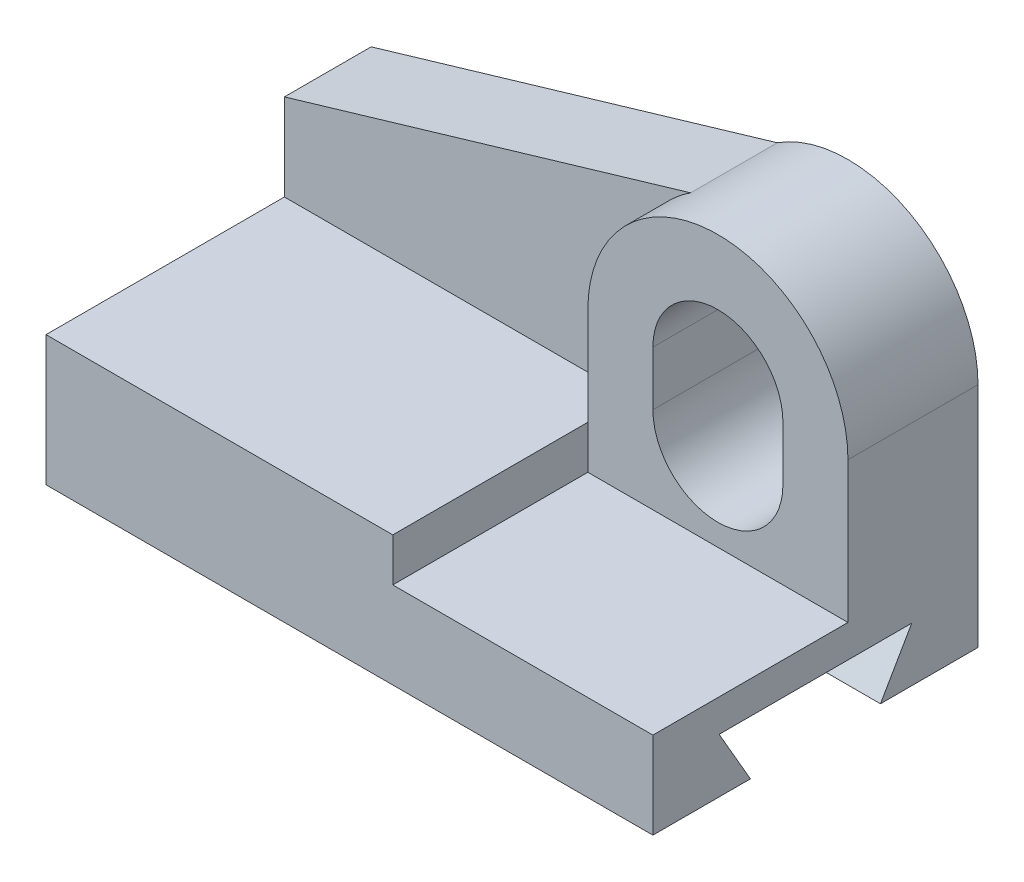
SolidWorks part; units mm, degrees
ref_plane "前视基准面" through (0, 0, 0) normal (0, 0, 1) x (1, 0, 0)
ref_plane "上视基准面" through (0, 0, 0) normal (0, 1, 0) x (1, 0, 0)
ref_plane "右视基准面" through (0, 0, 0) normal (1, 0, 0) x (0, 0, -1)
other "Configuration Table"
sketch "草图2" plane through (0, 0, 0) normal (0, 1, 0) x (1, 0, 0)
  line L1 (0, 0) -> (56, 0)
  line L2 (0, 0) -> (0, -30)
  line L3 (0, -30) -> (56, -30)
  line L4 (56, 0) -> (56, -30)
  dimension "D1" = 56
  dimension "D2" = 30
extrude "凸台-拉伸2" add sketch "草图2" along normal blind 12
sketch "草图4" plane through (0, 0, 0) normal (-1, 0, 0) x (0, 0, 1)
  line L0 (9, 0) -> (21, 0)
  line L1 (0, 0) -> (30, 0) construction
  line L2 (21, 0) -> (23.8868, 5)
  line L3 (23.8868, 5) -> (6.1132, 5)
  line L4 (6.1132, 5) -> (9, 0)
  point P5 (15, 0)
  dimension "D1" = 15
  dimension "D2" = 12
  dimension "D3" = 60
  dimension "D4" = 5
  dimension "D5" = 60
extrude "切除-拉伸1" cut sketch "草图4" against normal through all
sketch "草图6" plane through (0, 12, 0) normal (0, 1, 0) x (1, 0, 0)
  line L0 (0, 0) -> (0, -8)
  line L1 (0, 0) -> (0, -30) construction
  line L2 (0, -8) -> (56, -8)
  line L3 (56, -30) -> (56, 0) construction
  line L4 (56, -8) -> (56, 0)
  line L5 (56, 0) -> (0, 0) construction
  line L6 (56, 0) -> (0, 0)
  line L7 (56, 0) -> (32, 0)
  line L8 (32, 0) -> (32, -30)
  line L9 (0, -30) -> (56, -30) construction
  line L10 (32, -30) -> (56, -30)
  line L11 (56, -30) -> (56, 0)
extrude "切除-拉伸2" cut sketch "草图6" against normal blind 4 contours L7 L8 L10 L11
sketch "草图8" plane through (0, 12, 0) normal (0, 1, 0) x (1, 0, 0)
  line L0 (0, 0) -> (0, -8)
  line L1 (0, 0) -> (0, -30) construction
extrude "拉伸-薄壁1" add sketch "草图8" along normal blind 8 thin thin type one direction reverse wall 10
sketch "草图9" plane through (0, 8, 0) normal (0, 1, 0) x (1, 0, 0)
  line L0 (32, 0) -> (32, -12)
  line L1 (32, 0) -> (32, -30) construction
  line L2 (32, -12) -> (56, -12)
  line L3 (56, -30) -> (56, 0) construction
  line L4 (56, -12) -> (56, 0)
  line L5 (56, 0) -> (32, 0)
extrude "凸台-拉伸3" add sketch "草图9" along normal blind 13
sketch "草图10" plane through (0, 0, 12) normal (0, 0, 1) x (1, 0, 0)
  line L0 (32, 21) -> (56, 21) construction
  circle A0 centre (44, 21) radius 12
extrude "凸台-拉伸4" add sketch "草图10" against normal up to vertex (12 mm away) up to point (32, 21, 0)
sketch "草图13" plane through (0, 0, 0) normal (0, 0, -1) x (-1, 0, 0)
  line L0 (0, 20) -> (-44, 33)
  line L1 (0, 20) -> (0, 10)
  line L2 (0, 20) -> (0, 0) construction
  line L3 (0, 10) -> (-44, 10)
  line L4 (-44, 10) -> (-44.3405, 32.9952)
  line L12 (-32, 12) -> (-32, 21)
  line L13 (-56, 21) -> (-56, 0)
  line L14 (-56, 0) -> (0, 0)
  line L15 (0, 0) -> (0, 20)
  line L16 (0, 20) -> (-10, 20)
  line L17 (-10, 20) -> (-10, 12)
  line L18 (-10, 12) -> (-32, 12)
  arc A0 (-32, 21) -> (-56, 21) centre (-44, 21) ccw construction
  arc A2 (-32, 21) -> (-56, 21) centre (-44, 21) ccw
  arc A3 (-44, 33) -> (-44.3405, 32.9952) centre (-44, 21) ccw
  dimension "D1" = 0
extrude "凸台-拉伸5" add sketch "草图13" against normal offset from surface (8 mm away) 4 up to face at (41.6, 16.4, 12)
sketch "草图14" plane through (0, 0, 12) normal (0, 0, 1) x (1, 0, 0)
  line L1 (38, 21) -> (38, 16)
  line L2 (50, 21) -> (50, 16)
  arc A1 (50, 21) -> (38, 21) centre (44, 21) ccw
  arc A2 (56, 21) -> (32, 21) centre (44, 21) ccw construction
  arc A3 (38, 16) -> (50, 16) centre (44, 16) ccw
extrude "切除-拉伸3" cut sketch "草图14" against normal through all contours A1 L1 A3 L2
